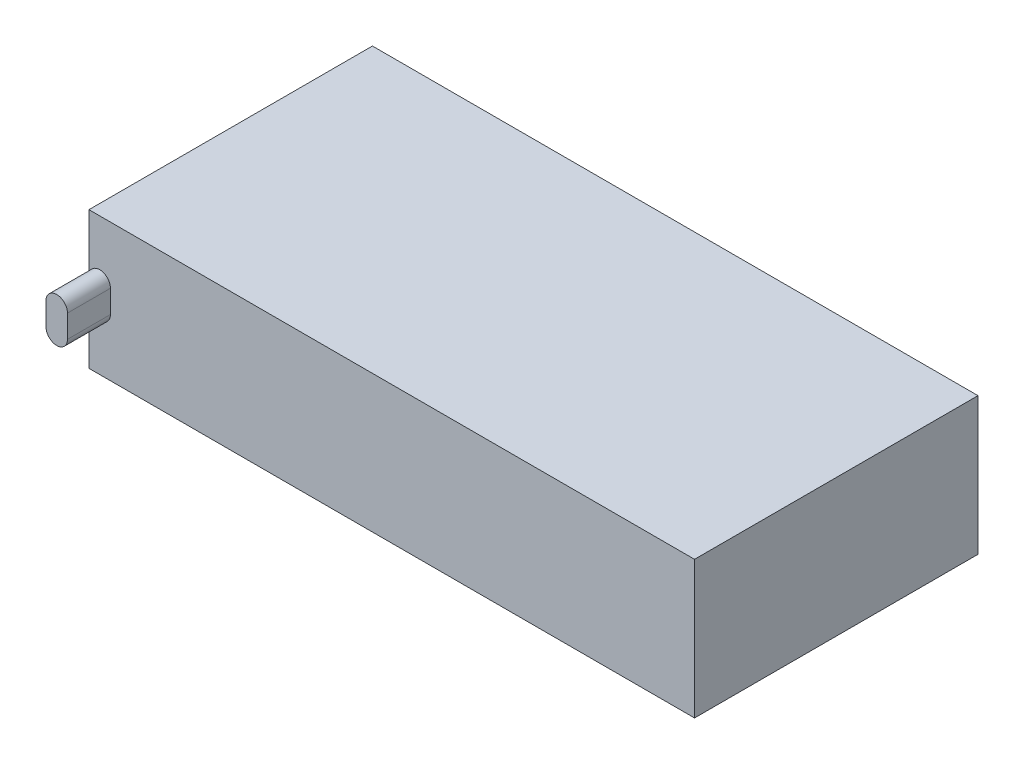
SolidWorks part; units mm, degrees
ref_plane "Front Plane" through (0, 0, 0) normal (0, 0, 1) x (1, 0, 0)
ref_plane "Top Plane" through (0, 0, 0) normal (0, 1, 0) x (1, 0, 0)
ref_plane "Right Plane" through (0, 0, 0) normal (1, 0, 0) x (0, 0, -1)
sketch "Sketch1" plane through (0, 0, 0) normal (1, 0, 0) x (0, 0, -1)
  line L1 (0, 0) -> (16.764, 0)
  line L2 (0, 0) -> (0, 8.128)
  line L3 (0, 8.128) -> (16.764, 8.128)
  line L4 (16.764, 0) -> (16.764, 8.128)
  dimension "D1" = 16.764
  dimension "D2" = 8.128
extrude "Boss-Extrude1" add sketch "Sketch1" along normal blind 35.814
sketch "Sketch2" plane through (0, 0, 0) normal (0, 0, 1) x (1, 0, 0)
  line L0 (0.635, 4.7365) -> (0.635, 3.3915) construction
  line L1 (1.27, 4.7365) -> (1.27, 3.3915)
  line L2 (0, 4.7365) -> (0, 3.3915)
  line L3 (0, 8.128) -> (0, 0) construction
  arc A0 (1.27, 4.7365) -> (0, 4.7365) centre (0.635, 4.7365) ccw
  arc A1 (0, 3.3915) -> (1.27, 3.3915) centre (0.635, 3.3915) ccw
  point P2 (0.635, 4.064)
  point P10 (0, 4.064)
  point P11 (0.635, 5.3715)
  point P12 (0.635, 2.7565)
  dimension "D1" = 2.6149
  dimension "D2" = 1.27
extrude "Boss-Extrude2" add sketch "Sketch2" along normal blind 2.54
